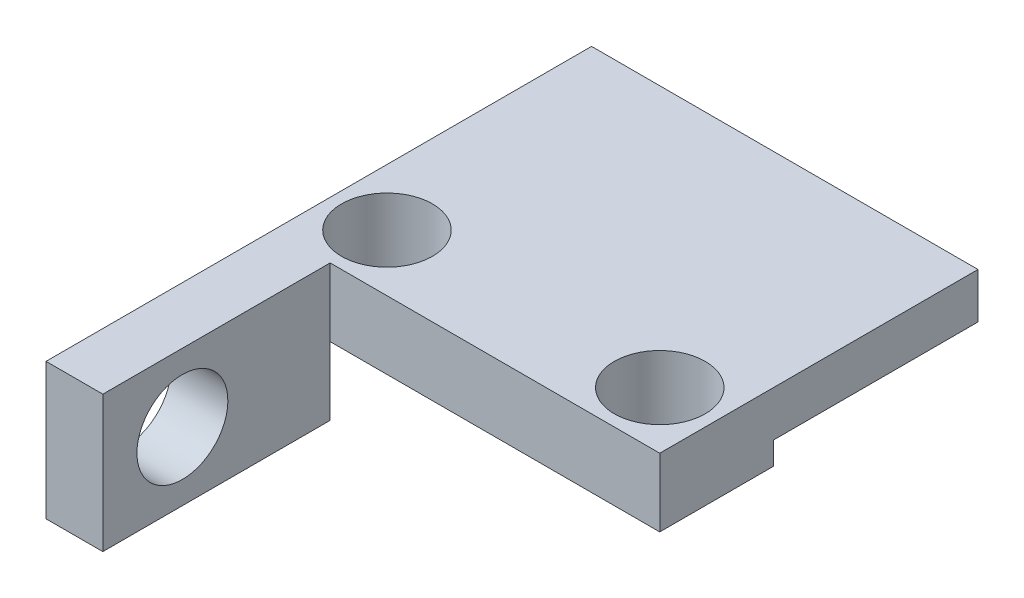
SolidWorks part; units mm, degrees
ref_plane "前视基准面" through (0, 0, 0) normal (0, 0, 1) x (1, 0, 0)
ref_plane "上视基准面" through (0, 0, 0) normal (0, 1, 0) x (1, 0, 0)
ref_plane "右视基准面" through (0, 0, 0) normal (1, 0, 0) x (0, 0, -1)
sketch "草图1" plane through (0, 0, 0) normal (0, 1, 0) x (1, 0, 0)
  line L0 (-14.0288, -4.1727) -> (-14.0288, 23.8273)
  line L1 (-14.0288, 23.8273) -> (19.9712, 23.8273)
  line L2 (19.9712, 23.8273) -> (19.9712, -4.1727)
  line L3 (19.9712, -4.1727) -> (-14.0288, -4.1727)
  dimension "D1" = 28
  dimension "D3" = 34
extrude "凸台-拉伸1" add sketch "草图1" along normal blind 6
sketch "草图2" plane through (19.9712, 0, 0) normal (1, 0, 0) x (0, 0, -1)
  line L0 (23.8273, 2) -> (5.8273, 2)
  line L2 (5.8273, 2) -> (5.8273, 0)
  line L4 (-4.1727, 0) -> (23.8273, 0) construction
  dimension "D1" = 18
  dimension "D2" = 2
extrude "切除-拉伸1" cut sketch "草图2" against normal through all and the other way through all
sketch "草图5" plane through (0, 0, 0) normal (0, -1, 0) x (1, 0, 0)
  line L0 (2.9712, -5.8273) -> (2.9712, 4.1727) construction
  line L1 (-14.0288, -5.8273) -> (19.9712, -5.8273) construction
  line L2 (-14.0288, 4.1727) -> (19.9712, 4.1727) construction
  line L3 (2.9712, 4.1727) -> (2.9712, -0.8273) construction
  line L4 (2.9712, -0.8273) -> (14.9712, -0.8273) construction
  line L5 (2.9712, -0.8273) -> (-9.0288, -0.8273) construction
  circle A0 centre (-9.0288, -0.8273) radius 4
  circle A1 centre (14.9712, -0.8273) radius 4
  dimension "D3" = 8
  dimension "D4" = 8
  dimension "D1" = 12
  dimension "D2" = 12
extrude "切除-拉伸3" cut sketch "草图5" against normal up to next
sketch "草图9" plane through (0, 0, 4.1727) normal (0, 0, 1) x (1, 0, 0)
  line L0 (2.9712, 6) -> (-9.0288, 6) construction
  line L1 (-14.0288, 6) -> (19.9712, 6) construction
  line L2 (-9.0288, 6) -> (-9.0288, -6)
  line L3 (-9.0288, -6) -> (-14.0288, -6)
  line L4 (-14.0288, -6) -> (-14.0288, 6)
  line L5 (-14.0288, 6) -> (-9.0288, 6)
  dimension "D1" = 12
  dimension "D2" = 12
extrude "凸台-拉伸4" add sketch "草图9" along normal blind 20
sketch "草图10" plane through (-9.0288, 0, 0) normal (1, 0, 0) x (0, 0, -1)
  line L0 (-24.1727, 0) -> (-17.1727, 0) construction
  line L1 (-24.1727, -6) -> (-24.1727, 6) construction
  circle A0 centre (-17.1727, 0) radius 4
  dimension "D2" = 8
  dimension "D1" = 7
extrude "切除-拉伸4" cut sketch "草图10" against normal up to next
